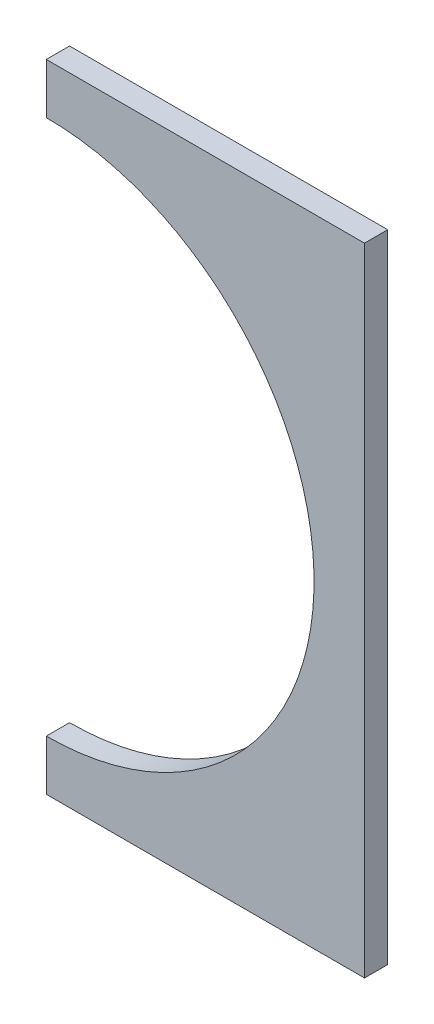
SolidWorks part; units mm, degrees
ref_plane "Спереди" through (0, 0, 0) normal (0, 0, 1) x (1, 0, 0)
ref_plane "Сверху" through (0, 0, 0) normal (0, 1, 0) x (1, 0, 0)
ref_plane "Справа" through (0, 0, 0) normal (1, 0, 0) x (0, 0, -1)
other "Configuration Table"
sketch "Эскиз1" plane through (0, 0, 0) normal (0, 0, 1) x (1, 0, 0)
  line L1 (0, 82.05) -> (82.05, 82.05)
  line L2 (0, 82.05) -> (0, -82.05)
  line L3 (0, -82.05) -> (82.05, -82.05)
  line L4 (82.05, 82.05) -> (82.05, -82.05)
  circle A0 centre (0, 0) radius 69.05
  point P7 (69.05, 0)
  point P8 (0, 69.05)
  point P9 (0, -69.05)
  dimension "D1" = 138.1
  dimension "D2" = 13
  dimension "D3" = 13
  dimension "D4" = 13
extrude "Бобышка-Вытянуть1" add sketch "Эскиз1" along normal blind 6 contours A0 L2 L3 L4 L1
equation "\"D3@Эскиз1\"=\"D2@Эскиз1\""
equation "\"D4@Эскиз1\"=\"D2@Эскиз1\""
